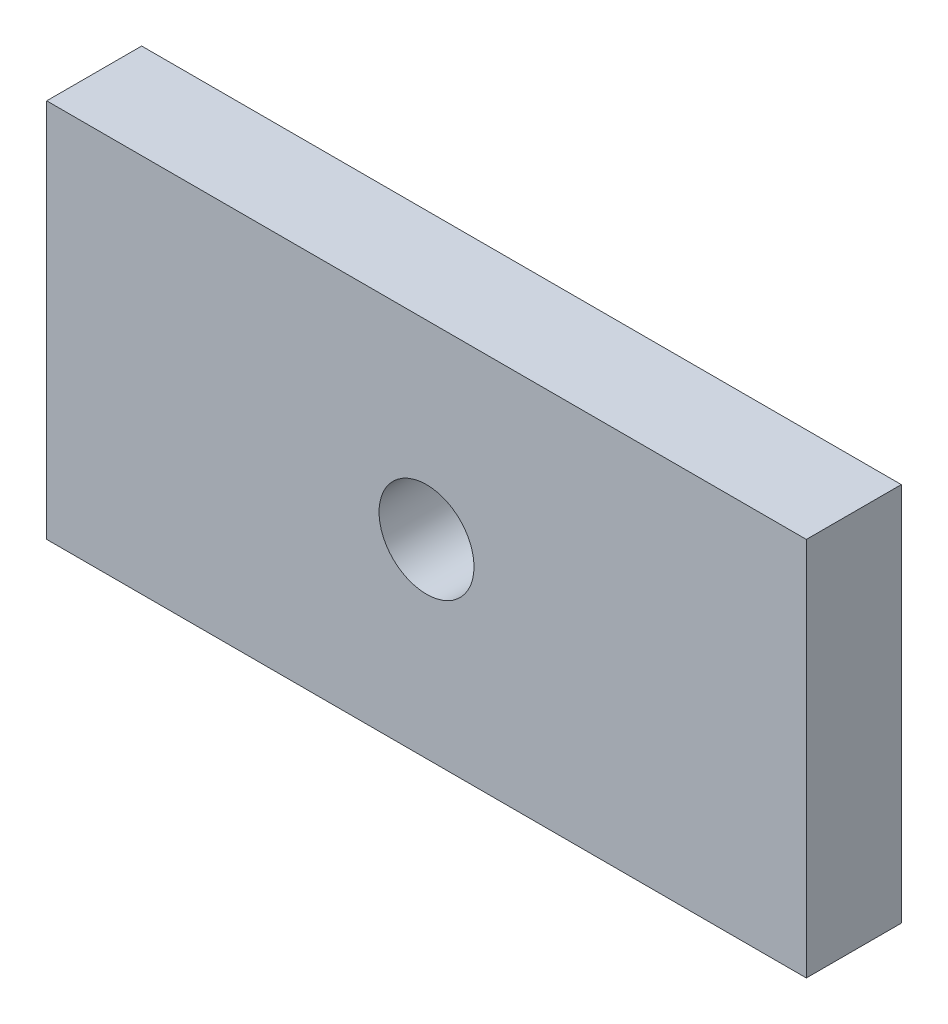
SolidWorks part; units mm, degrees
ref_plane "Front Plane" through (0, 0, 0) normal (0, 0, 1) x (1, 0, 0)
ref_plane "Top Plane" through (0, 0, 0) normal (0, 1, 0) x (1, 0, 0)
ref_plane "Right Plane" through (0, 0, 0) normal (1, 0, 0) x (0, 0, -1)
sketch "Sketch1" plane through (0, 0, 0) normal (0, 0, 1) x (1, 0, 0)
  line L1 (-40, -20) -> (40, -20)
  line L2 (-40, -20) -> (-40, 20)
  line L3 (-40, 20) -> (40, 20)
  line L4 (40, -20) -> (40, 20)
  line L5 (-40, -20) -> (40, 20) construction
  line L6 (-40, 20) -> (40, -20) construction
  circle A0 centre (0, 0) radius 5
  point P0 (0, 0)
  dimension "D3" = 10
  dimension "D1" = 80
  dimension "D2" = 40
extrude "Boss-Extrude1" add sketch "Sketch1" along normal blind 10
